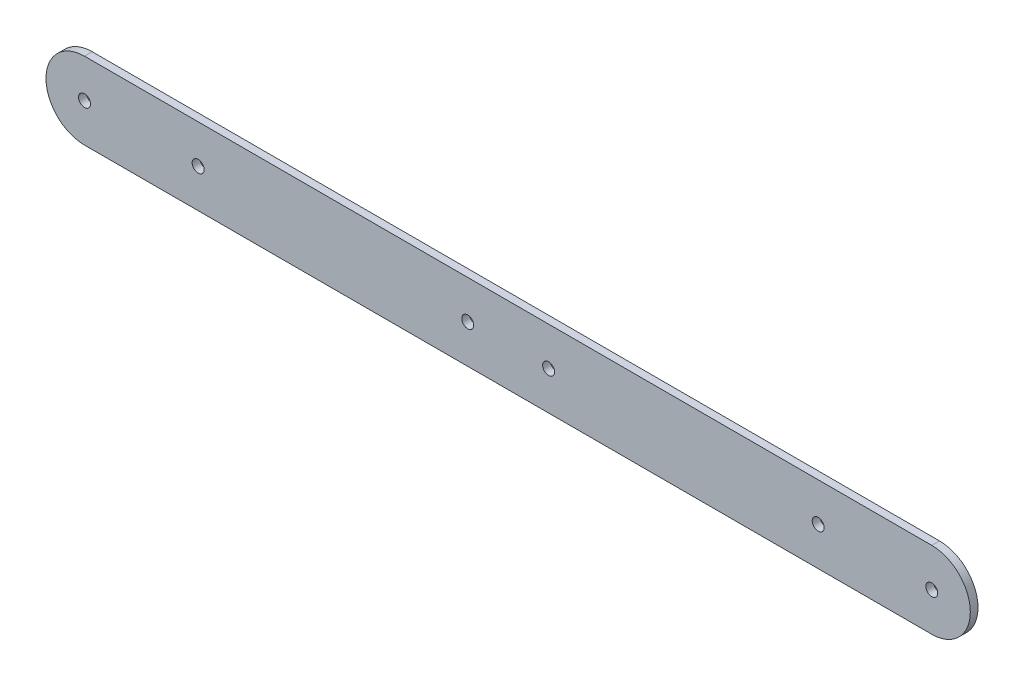
SolidWorks part; units mm, degrees
ref_plane "前视基准面" through (0, 0, 0) normal (0, 0, 1) x (1, 0, 0)
ref_plane "上视基准面" through (0, 0, 0) normal (0, 1, 0) x (1, 0, 0)
ref_plane "右视基准面" through (0, 0, 0) normal (1, 0, 0) x (0, 0, -1)
other "Configuration Table"
sketch "草图1" plane through (0, 0, 0) normal (0, 0, 1) x (1, 0, 0)
  line L0 (0, 0) -> (0, -13.4678) construction
  line L63 (-110, 10) -> (110, 10)
  line L65 (-110, -10) -> (110, -10)
  line L67 (-110, 10) -> (110, -10) construction
  line L68 (-110, -10) -> (110, 10) construction
  circle A0 centre (10.5, 0) radius 1.55
  circle A14 centre (80.5, 0) radius 1.55
  circle A15 centre (-80.5, 0) radius 1.55
  circle A16 centre (-10.5, 0) radius 1.55
  arc A17 (-110, 10) -> (-110, -10) centre (-110, 0) ccw
  circle A18 centre (-110, 0) radius 1.55
  arc A19 (110, 10) -> (110, -10) centre (110, 0) cw
  circle A20 centre (110, 0) radius 1.55
  point P68 (5.8393, 0)
  point P100 (-5.8393, 0)
  dimension "D4" = 80.5
  dimension "D5" = 3.1
  dimension "D6" = 3.1
  dimension "D7" = 3.1
  dimension "D1" = 220
  dimension "D2" = 20
  dimension "D3" = 10.5
extrude "凸台-拉伸1" add sketch "草图1" along normal blind 2
